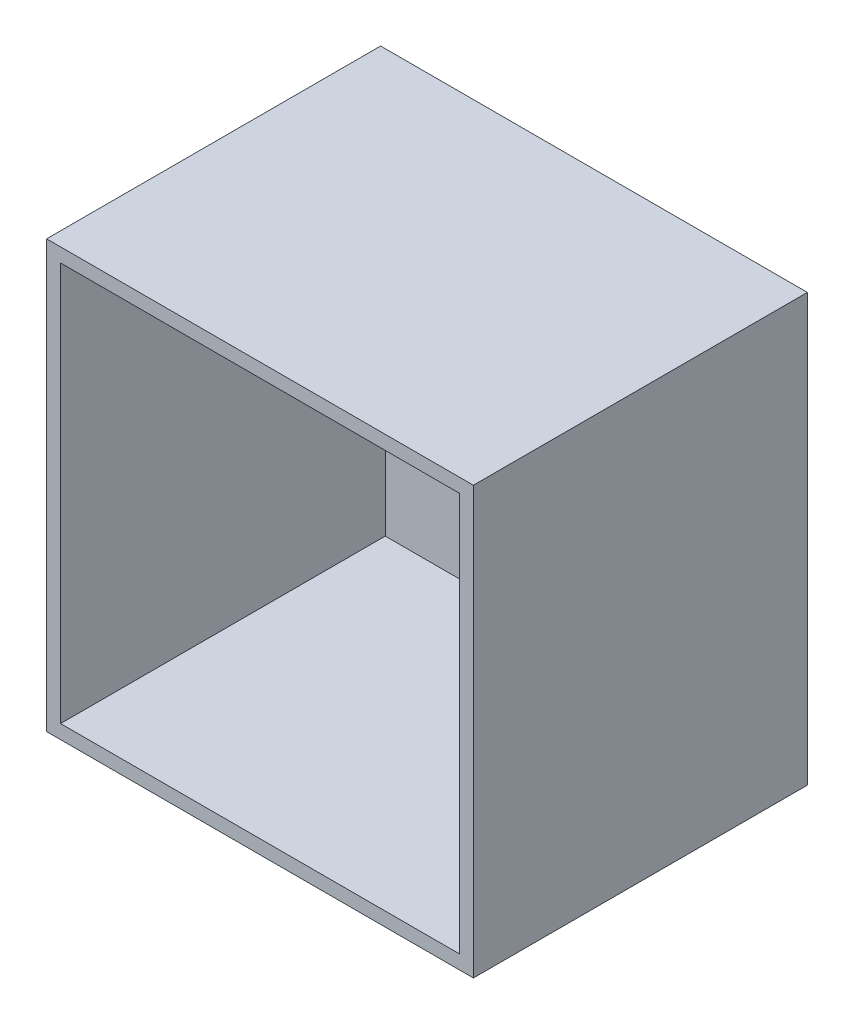
SolidWorks part; units mm, degrees
ref_plane "Plan de face" through (0, 0, 0) normal (0, 0, 1) x (1, 0, 0)
ref_plane "Plan de dessus" through (0, 0, 0) normal (0, 1, 0) x (1, 0, 0)
ref_plane "Plan de droite" through (0, 0, 0) normal (1, 0, 0) x (0, 0, -1)
sketch "Esquisse1" plane through (0, 0, 0) normal (0, 0, 1) x (1, 0, 0)
  line L1 (-23, 23) -> (23, 23)
  line L2 (-23, 23) -> (-23, -23)
  line L3 (-23, -23) -> (23, -23)
  line L4 (23, 23) -> (23, -23)
  line L5 (-23, 23) -> (23, -23) construction
  line L6 (-23, -23) -> (23, 23) construction
  point P0 (0, 0)
  dimension "D1" = 46
  dimension "D2" = 46
extrude "Boss.-Extru.1" add sketch "Esquisse1" along normal blind 36
sketch "Esquisse2" plane through (0, 0, 36) normal (0, 0, 1) x (1, 0, 0)
  line L1 (-21.5, 21.5) -> (21.5, 21.5)
  line L2 (-21.5, 21.5) -> (-21.5, -21.5)
  line L3 (-21.5, -21.5) -> (21.5, -21.5)
  line L4 (21.5, 21.5) -> (21.5, -21.5)
  line L5 (-21.5, 21.5) -> (21.5, -21.5) construction
  line L6 (-21.5, -21.5) -> (21.5, 21.5) construction
  point P0 (0, 0)
  dimension "D1" = 43
  dimension "D2" = 43
extrude "Enlèv. mat.-Extru.1" cut sketch "Esquisse2" against normal blind 35
sketch "Esquisse3" plane through (0, 0, 0) normal (0, 0, -1) x (-1, 0, 0)
  circle A0 centre (0, 0) radius 10
extrude "Enlèv. mat.-Extru.2" cut sketch "Esquisse3" against normal blind 35
